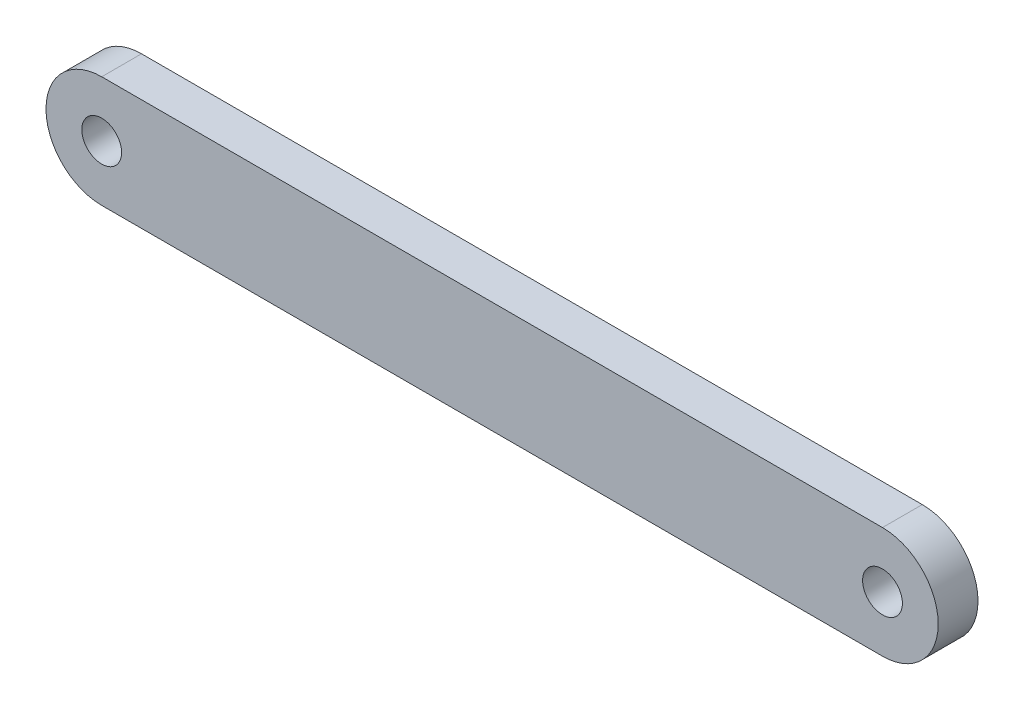
SolidWorks part; units mm, degrees
ref_plane "Front Plane" through (0, 0, 0) normal (0, 0, 1) x (1, 0, 0)
ref_plane "Top Plane" through (0, 0, 0) normal (0, 1, 0) x (1, 0, 0)
ref_plane "Right Plane" through (0, 0, 0) normal (1, 0, 0) x (0, 0, -1)
sketch "Sketch2" plane through (0, 0, 0) normal (0, 0, 1) x (1, 0, 0)
  line L0 (-63.1952, -8.8071) -> (61.3888, -8.8071)
  line L1 (-63.1952, 8.9729) -> (61.3888, 8.9729)
  line L2 (-63.1952, -8.8071) -> (61.3888, 8.9729) construction
  line L3 (-63.1952, 8.9729) -> (61.3888, -8.8071) construction
  arc A0 (-63.1952, 8.9729) -> (-63.1952, -8.8071) centre (-63.1952, 0.0829) ccw
  arc A1 (61.3888, 8.9729) -> (61.3888, -8.8071) centre (61.3888, 0.0829) cw
  circle A2 centre (-63.1952, 0.0829) radius 3.175
  circle A3 centre (61.3888, 0.0829) radius 3.175
  point P0 (-0.9032, 0.0829)
  dimension "D3" = 6.35
  dimension "D1" = 124.584
  dimension "D2" = 17.78
extrude "Boss-Extrude2" add sketch "Sketch2" along normal blind 6.35
